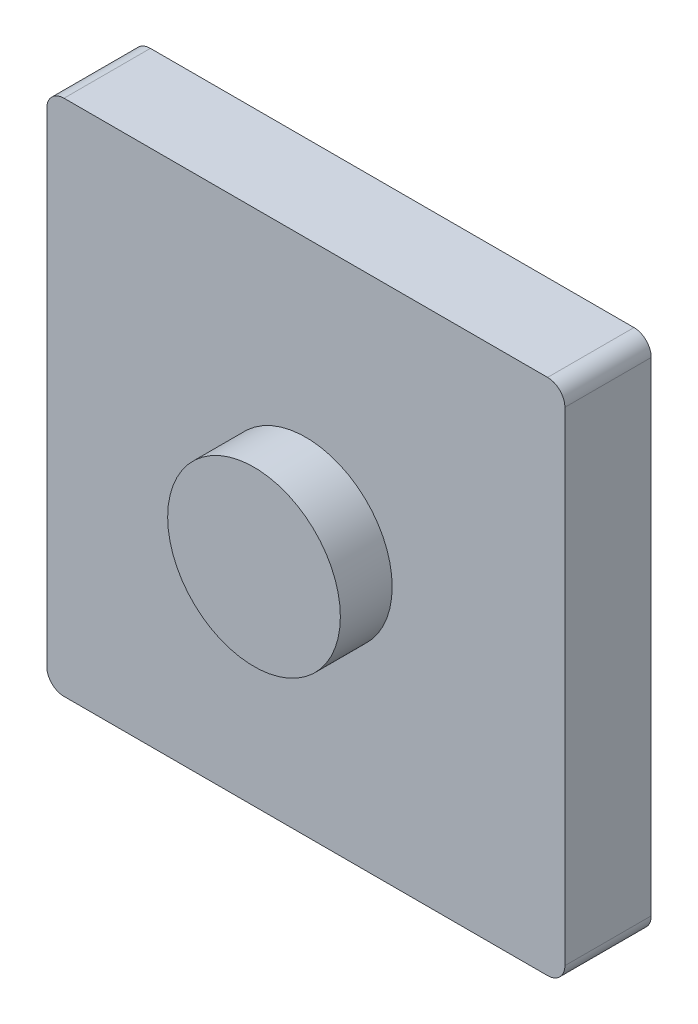
SolidWorks part; units mm, degrees
ref_plane "Front Plane" through (0, 0, 0) normal (0, 0, 1) x (1, 0, 0)
ref_plane "Top Plane" through (0, 0, 0) normal (0, 1, 0) x (1, 0, 0)
ref_plane "Right Plane" through (0, 0, 0) normal (1, 0, 0) x (0, 0, -1)
sketch "Sketch1" plane through (0, 0, 0) normal (0, 0, 1) x (1, 0, 0)
  line L1 (1, 0) -> (29, 0)
  line L2 (0, 1) -> (0, 29)
  line L3 (1, 30) -> (29, 30)
  line L4 (30, 1) -> (30, 29)
  arc A0 (1, 0) -> (0, 1) centre (1, 1) cw
  arc A1 (29, 0) -> (30, 1) centre (29, 1) ccw
  arc A2 (29, 30) -> (30, 29) centre (29, 29) cw
  arc A3 (0, 29) -> (1, 30) centre (1, 29) cw
  point P7 (0, 0)
  point P12 (30, 30)
  point P15 (0, 30)
  dimension "D3" = 1
  dimension "D1" = 30
  dimension "D2" = 30
extrude "Boss-Extrude1" add sketch "Sketch1" along normal blind 5
sketch "Sketch2" plane through (0, 0, 5) normal (0, 0, 1) x (1, 0, 0)
  line L0 (0, 29) -> (0, 1) construction
  line L1 (29, 30) -> (1, 30) construction
  circle A0 centre (15, 15) radius 5
  dimension "D1" = 10
  dimension "D2" = 15
  dimension "D3" = 15
extrude "Boss-Extrude2" add sketch "Sketch2" along normal blind 3
